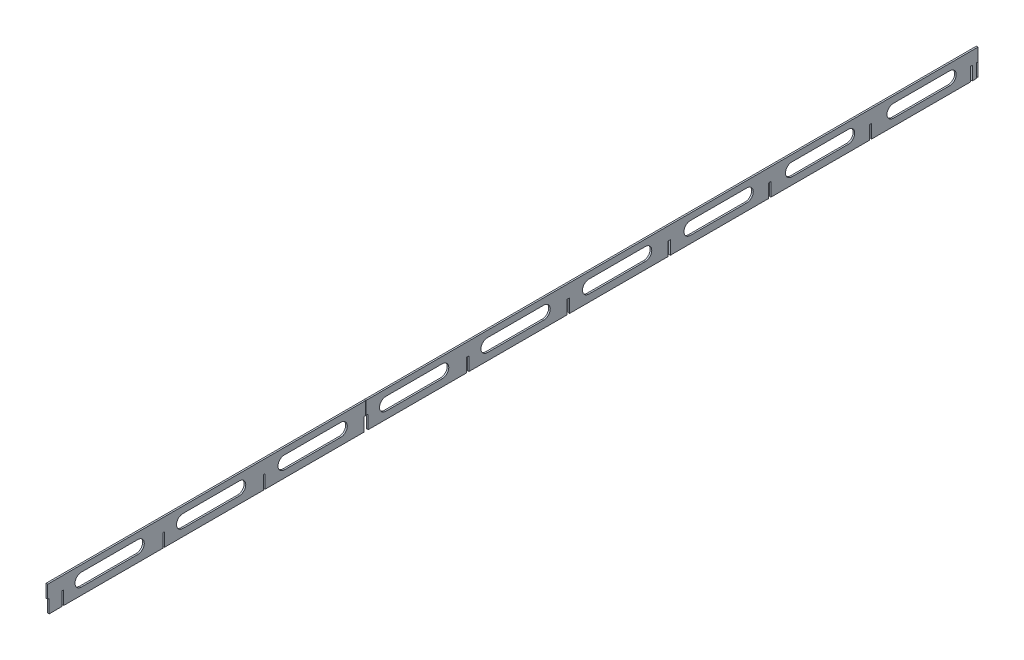
SolidWorks part; units mm, degrees
material "轻木"
ref_plane "前视基准面" through (0, 0, 0) normal (0, 0, 1) x (1, 0, 0)
ref_plane "上视基准面" through (0, 0, 0) normal (0, 1, 0) x (1, 0, 0)
ref_plane "右视基准面" through (0, 0, 0) normal (1, 0, 0) x (0, 0, -1)
other "Configuration Table"
sketch "草图1" plane through (0, 0, 0) normal (0, 0, 1) x (1, 0, 0)
  line L1 (-44.1255, 21.6473) -> (-46.1255, 21.6473)
  line L2 (-44.1255, 21.6473) -> (-44.1255, -11.2586)
  line L3 (-44.1255, -11.2586) -> (-46.1255, -11.2586)
  line L4 (-46.1255, 21.6473) -> (-46.1255, -11.2586)
  dimension "D1" = 2
extrude "凸台-拉伸1" add sketch "草图1" along normal blind 1155
sketch "草图2" plane through (-46.1255, 0, 0) normal (-1, 0, 0) x (0, 0, 1)
  line L0 (1155, -11.2586) -> (0, -11.2586) construction
  line L1 (7.01, -11.2586) -> (9.01, -11.2586)
  line L2 (7.01, -11.2586) -> (7.01, 5.5696)
  line L3 (7.01, 5.5696) -> (9.01, 5.5696)
  line L4 (9.01, -11.2586) -> (9.01, 5.5696)
  line L5 (260, -11.2586) -> (260, 5.5696)
  line L30 (7.01, -11.2586) -> (132.01, -11.2586) construction
  line L32 (2, -11.2586) -> (0.01, -11.2586)
  line L33 (2, -11.2586) -> (2, 5.5696)
  line L34 (2, 5.5696) -> (0.01, 5.5696)
  line L35 (0.01, -11.2586) -> (0.01, 5.5696)
  line L55 (257.01, -11.2586) -> (257.01, 5.5696)
  line L61 (35, 5.6473) -> (105, 5.6473) construction
  line L62 (35, 13.6473) -> (105, 13.6473)
  line L63 (257.01, 5.5696) -> (260, 5.5696)
  line L64 (257.01, -11.2586) -> (260, -11.2586)
  line L66 (385, -11.2586) -> (385, 5.5696)
  line L67 (35, -2.3527) -> (105, -2.3527)
  line L68 (382.01, -11.2586) -> (382.01, 5.5696)
  line L69 (1155, 21.6473) -> (0, 21.6473) construction
  line L70 (0, 21.6473) -> (0, -11.2586) construction
  line L71 (161, 5.6473) -> (231, 5.6473) construction
  line L72 (161, 13.6473) -> (231, 13.6473)
  line L73 (161, -2.3527) -> (231, -2.3527)
  line L74 (287, 5.6473) -> (357, 5.6473) construction
  line L75 (287, 13.6473) -> (357, 13.6473)
  line L76 (287, -2.3527) -> (357, -2.3527)
  line L77 (413, 5.6473) -> (483, 5.6473) construction
  line L78 (413, 13.6473) -> (483, 13.6473)
  line L79 (413, -2.3527) -> (483, -2.3527)
  line L80 (539, 5.6473) -> (609, 5.6473) construction
  line L81 (539, 13.6473) -> (609, 13.6473)
  line L82 (539, -2.3527) -> (609, -2.3527)
  line L83 (665, 5.6473) -> (735, 5.6473) construction
  line L84 (665, 13.6473) -> (735, 13.6473)
  line L85 (665, -2.3527) -> (735, -2.3527)
  line L86 (791, 5.6473) -> (861, 5.6473) construction
  line L87 (791, 13.6473) -> (861, 13.6473)
  line L88 (791, -2.3527) -> (861, -2.3527)
  line L89 (917, 5.6473) -> (987, 5.6473) construction
  line L90 (917, 13.6473) -> (987, 13.6473)
  line L91 (917, -2.3527) -> (987, -2.3527)
  line L92 (1043, 5.6473) -> (1113, 5.6473) construction
  line L93 (1043, 13.6473) -> (1113, 13.6473)
  line L94 (1043, -2.3527) -> (1113, -2.3527)
  line L98 (35, 5.6473) -> (161, 5.6473) construction
  line L102 (382.01, 5.5696) -> (385, 5.5696)
  line L103 (382.01, -11.2586) -> (385, -11.2586)
  line L104 (510, -11.2586) -> (510, 5.5696)
  line L105 (507.01, -11.2586) -> (507.01, 5.5696)
  line L106 (507.01, 5.5696) -> (510, 5.5696)
  line L107 (507.01, -11.2586) -> (510, -11.2586)
  line L108 (132.01, -11.2586) -> (135, -11.2586)
  line L109 (132.01, -11.2586) -> (132.01, 5.5696)
  line L110 (132.01, 5.5696) -> (135, 5.5696)
  line L111 (135, -11.2586) -> (135, 5.5696)
  line L112 (635, -11.2586) -> (635, 5.5696)
  line L113 (632.01, -11.2586) -> (632.01, 5.5696)
  line L114 (632.01, 5.5696) -> (635, 5.5696)
  line L115 (632.01, -11.2586) -> (635, -11.2586)
  line L116 (760, -11.2586) -> (760, 5.5696)
  line L117 (757.01, -11.2586) -> (757.01, 5.5696)
  line L118 (757.01, 5.5696) -> (760, 5.5696)
  line L119 (757.01, -11.2586) -> (760, -11.2586)
  line L120 (135, -11.2586) -> (260, -11.2586) construction
  line L121 (762, -5.3019) -> (762, 21.5705) construction
  line L122 (760, -11.2586) -> (762, -11.2586)
  line L123 (760, -11.2586) -> (760, 5.5696)
  line L124 (760, 5.5696) -> (762, 5.5696)
  line L125 (762, -11.2586) -> (762, 5.5696)
  line L126 (762, 21.7492) -> (760, 21.7492) construction
  line L127 (759.9, 5.5696) -> (760.1, 5.5696)
  line L128 (759.9, 5.5696) -> (759.9, 21.7492)
  line L129 (759.9, 21.7492) -> (760.1, 21.7492)
  line L130 (760.1, 5.5696) -> (760.1, 21.7492)
  line L132 (1153, 21.5705) -> (1153, -5.3019) construction
  line L133 (1155, -11.2586) -> (1153, -11.2586)
  line L134 (1155, -11.2586) -> (1155, 5.5696)
  line L135 (1155, 5.5696) -> (1153, 5.5696)
  line L136 (1153, -11.2586) -> (1153, 5.5696)
  line L137 (1155, 5.5696) -> (1153, 5.5696) construction
  line L138 (885, -11.2586) -> (885, 5.5696)
  line L139 (885, 5.5696) -> (887, 5.5696)
  line L140 (885, -11.2586) -> (887, -11.2586)
  line L141 (887, -11.2586) -> (887, 5.5696)
  line L142 (1010, -11.2586) -> (1010, 5.5696)
  line L143 (1010, 5.5696) -> (1012, 5.5696)
  line L144 (1010, -11.2586) -> (1012, -11.2586)
  line L145 (1012, -11.2586) -> (1012, 5.5696)
  line L146 (1135, -11.2586) -> (1135, 5.5696)
  line L147 (1135, 5.5696) -> (1137, 5.5696)
  line L148 (1135, -11.2586) -> (1137, -11.2586)
  line L149 (1137, -11.2586) -> (1137, 5.5696)
  line L150 (760, -11.2586) -> (885, -11.2586) construction
  line L151 (2, -13.0856) -> (2, -7.0333) construction
  arc A0 (35, 13.6473) -> (35, -2.3527) centre (35, 5.6473) ccw
  arc A1 (105, -2.3527) -> (105, 13.6473) centre (105, 5.6473) ccw
  arc A2 (161, 13.6473) -> (161, -2.3527) centre (161, 5.6473) ccw
  arc A3 (231, -2.3527) -> (231, 13.6473) centre (231, 5.6473) ccw
  arc A4 (287, 13.6473) -> (287, -2.3527) centre (287, 5.6473) ccw
  arc A5 (357, -2.3527) -> (357, 13.6473) centre (357, 5.6473) ccw
  arc A6 (413, 13.6473) -> (413, -2.3527) centre (413, 5.6473) ccw
  arc A7 (483, -2.3527) -> (483, 13.6473) centre (483, 5.6473) ccw
  arc A8 (539, 13.6473) -> (539, -2.3527) centre (539, 5.6473) ccw
  arc A9 (609, -2.3527) -> (609, 13.6473) centre (609, 5.6473) ccw
  arc A10 (665, 13.6473) -> (665, -2.3527) centre (665, 5.6473) ccw
  arc A11 (735, -2.3527) -> (735, 13.6473) centre (735, 5.6473) ccw
  arc A12 (791, 13.6473) -> (791, -2.3527) centre (791, 5.6473) ccw
  arc A13 (861, -2.3527) -> (861, 13.6473) centre (861, 5.6473) ccw
  arc A14 (917, 13.6473) -> (917, -2.3527) centre (917, 5.6473) ccw
  arc A15 (987, -2.3527) -> (987, 13.6473) centre (987, 5.6473) ccw
  arc A16 (1043, 13.6473) -> (1043, -2.3527) centre (1043, 5.6473) ccw
  arc A17 (1113, -2.3527) -> (1113, 13.6473) centre (1113, 5.6473) ccw
  point P74 (70, 5.6473)
  point P89 (196, 5.6473)
  point P96 (322, 5.6473)
  point P103 (448, 5.6473)
  point P110 (574, 5.6473)
  point P117 (700, 5.6473)
  point P124 (826, 5.6473)
  point P131 (952, 5.6473)
  point P138 (1078, 5.6473)
  line M3 (0, -11.2586) -> (1155, -11.2586)
  line M4 (1155, -11.2586) -> (1155, 21.6473)
  line M5 (1155, 21.6473) -> (0, 21.6473)
  dimension "D5" = 8
  dimension "D2" = 125
  dimension "D3" = 125
  dimension "D4" = 16
  dimension "D6" = 70
  dimension "D7" = 70
  dimension "D8" = 126
  dimension "D11" = 0.1
  dimension "D12" = 0.2
  dimension "D13" = 125
  dimension "D14" = 7
  dimension "D15" = 2
  dimension "D10" = 6
  dimension "D9" = 9
extrude "切除-拉伸1" cut sketch "草图2" against normal blind 3 contours L35 L33 L34 M3 | L4 L3 L2 M3 | L67 A1 L62 A0 | L111 L110 L109 M3 | L73 A3 L72 A2 | L63 L55 L5 M3 | L76 A5 L75 A4 | L102 L68 L66 M3 | L79 A7 L78 A6 | L106 L105 L104 M3 | L82 A9 L81 A8 | L114 L113 L112 M3 | L85 A11 L84 A10 | L118 L117 L116 M3 | L125 L124 L116 M3 | L124 L130 L128 L118 M5 | L88 A13 L87 A12 | L141 L139 L138 M3 | L91 A15 L90 A14 | L145 L143 L142 M3 | L94 A17 L93 A16 | L149 L147 L146 M3 | L136 L135 M3 M4
